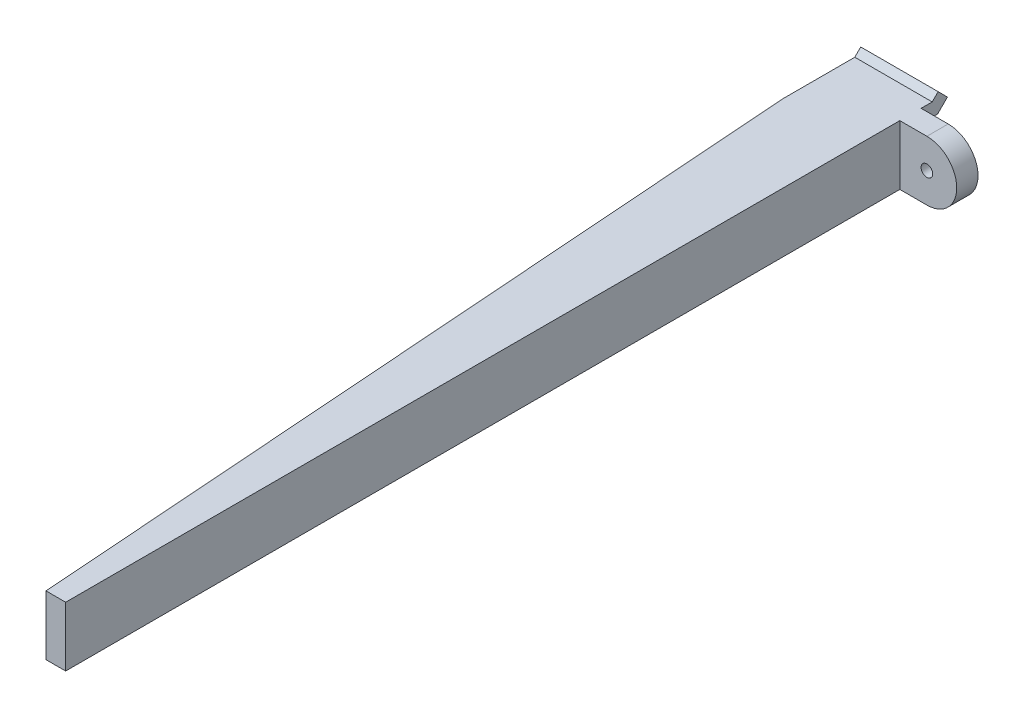
SolidWorks part; units mm, degrees
ref_plane "Front Plane" through (0, 0, 0) normal (0, 0, 1) x (1, 0, 0)
ref_plane "Top Plane" through (0, 0, 0) normal (0, 1, 0) x (1, 0, 0)
ref_plane "Right Plane" through (0, 0, 0) normal (1, 0, 0) x (0, 0, -1)
sketch "Sketch2" plane through (0, 0, 0) normal (0, 0, 1) x (1, 0, 0)
  line L0 (0, 5.9203) -> (0, 8.9503) construction
  line L1 (-5, -5.8182) -> (5, -5.8182)
  line L2 (-5, -5.8182) -> (-5, 8.9503)
  line L3 (-5, 8.9503) -> (5, 8.9503)
  line L4 (5, -5.8182) -> (5, 8.9503)
  line L5 (89.0703, 8.9503) -> (109.0703, 8.9503) construction
  line L7 (33.2703, 5.9203) -> (-18.7297, 5.9203) construction
  line L8 (0, -5.8182) -> (0, -2.7882) construction
  point P0 (0, 0)
  dimension "D1" = 10
extrude "Boss-Extrude1" add sketch "Sketch2" along normal blind 5
sketch "Sketch8" plane through (-5, 0, 0) normal (-1, 0, 0) x (0, 0, 1)
  line L6 (-0.15, 5.7703) -> (0, 5.7703)
  line L7 (0, 8.9503) -> (0, -5.8182) construction
  line L8 (0, 5.7703) -> (0, 4.0703)
  line L9 (0, 4.0703) -> (-0.15, 4.0703)
  line L11 (-0.15, -1.9297) -> (0, -1.9297)
  line L12 (-2.1379, 4.0703) -> (-0.15, 4.0703)
  line L13 (-0.15, 4.0703) -> (-0.15, 5.7703)
  line L14 (-0.15, 5.7703) -> (-1.4337, 5.7703)
  line L15 (-1.4337, 5.7703) -> (-2.2, 6.5366)
  line L16 (-2.2, 6.5366) -> (-3.4021, 5.3345)
  line L17 (-3.4021, 5.3345) -> (-2.1379, 4.0703)
  line L18 (-2.1379, 4.0703) -> (-0.15, 4.0703)
  line L20 (-0.15, 5.7703) -> (-1.4337, 5.7703)
  line L21 (-1.4337, 5.7703) -> (-2.2, 6.5366)
  line L22 (-2.2, 6.5366) -> (-3.4021, 5.3345)
  line L23 (-3.4021, 5.3345) -> (-2.1379, 4.0703)
  line L24 (-2.1379, -1.9297) -> (-0.15, -1.9297)
  line L25 (-0.15, -1.9297) -> (-0.15, -0.2297)
  line L26 (-0.15, -0.2297) -> (-1.4337, -0.2297)
  line L27 (-1.4337, -0.2297) -> (-2.2, 0.5366)
  line L28 (-2.2, 0.5366) -> (-3.4021, -0.6655)
  line L29 (-3.4021, -0.6655) -> (-2.1379, -1.9297)
  line L30 (-2.1379, -1.9297) -> (-0.15, -1.9297)
  line L32 (-0.15, -0.2297) -> (-1.4337, -0.2297)
  line L33 (-1.4337, -0.2297) -> (-2.2, 0.5366)
  line L34 (-2.2, 0.5366) -> (-3.4021, -0.6655)
  line L35 (-3.4021, -0.6655) -> (-2.1379, -1.9297)
  line L37 (-0.15, -0.2297) -> (0, -0.2297)
  line L38 (0, -1.9297) -> (0, -0.2297)
  dimension "D1" = 0.15
  dimension "D2" = 0.15
extrude "Boss-Extrude4" add sketch "Sketch8" against normal up to surface (10 mm away) up to face at (5, 1.566, 2.5)
sketch "Sketch9" plane through (0, 0, 0) normal (0, 0, -1) x (-1, 0, 0)
  line L4 (-5, 8.9503) -> (-5, 5.7703)
  line L5 (-5, 5.7703) -> (5, 5.7703)
  line L6 (5, 5.7703) -> (5, 8.9503)
  line L7 (5, 8.9503) -> (-5, 8.9503)
  line L8 (-5, 8.9503) -> (-5, 5.7703)
  line L10 (5, 5.7703) -> (5, 8.9503)
  line L11 (5, 8.9503) -> (-5, 8.9503)
  line L16 (5, -1.9297) -> (-5, -1.9297)
  line L17 (-5, -1.9297) -> (-5, -5.8182)
  line L18 (-5, -5.8182) -> (5, -5.8182)
  line L19 (5, -5.8182) -> (5, -1.9297)
  line L21 (-5, -1.9297) -> (-5, -5.8182)
  line L22 (-5, -5.8182) -> (5, -5.8182)
  line L23 (5, -5.8182) -> (5, -1.9297)
  line L26 (-5, 5.7703) -> (5, 5.7703)
  line L27 (5, -1.9297) -> (-5, -1.9297)
  dimension "D1" = 0
  dimension "D2" = 0
extrude "Cut-Extrude3" cut sketch "Sketch9" against normal blind 5
sketch "Sketch10" plane through (0, 5.7703, 0) normal (0, 1, 0) x (1, 0, 0)
  line L0 (-5, -5) -> (-5, -10.5)
  line L1 (-5, -10.5) -> (1.3524, -55.7)
  line L2 (1.3524, -55.7) -> (6.3524, -55.7)
  line L3 (-5, -5) -> (5, -5)
  line L4 (-120.9789, 453.7107) -> (412.3545, 453.7107) construction
  line L5 (6.3524, -55.7) -> (6.3524, -49.2)
  line L6 (5, -5) -> (5, -14)
  arc A1 (5, -14) -> (6.3524, -49.2) centre (39.6089, -30.2962) ccw
  dimension "D1" = 172
  dimension "D2" = 45.2
  dimension "D3" = 5
  dimension "D4" = 6.5
  dimension "D5" = 5.5
  dimension "D6" = 9
extrude "Boss-Extrude5" add sketch "Sketch10" against normal up to surface (7.7 mm away) up to face at (0, -1.9297, 1.4311)
ref_plane "Plane1" through (0, 0, 2.75) normal (0, 0, 1) x (1, 0, 0)
sketch "Sketch12" plane through (0, 0, 0) normal (0, 0, 1) x (1, 0, 0)
  line L0 (5, 5.7703) -> (8.5, 5.7703)
  line L1 (8.5, -1.9297) -> (5, -1.9297)
  line L2 (5, -1.9297) -> (5, 5.7703)
  line L3 (1.3524, 5.7703) -> (6.3524, 5.7703) construction
  line L4 (1.3524, -1.9297) -> (6.3524, -1.9297) construction
  line L5 (5, 5.3345) -> (5, 6.5366) construction
  line L6 (6.3524, 5.7703) -> (1.3552, 5.7703) construction
  arc A0 (8.5, 5.7703) -> (8.5, -1.9297) centre (8.5, 1.9203) cw
  circle A1 centre (8.5, 1.9203) radius 0.75
  dimension "D1" = 1.5
  dimension "D2" = 3.5
extrude "Boss-Extrude7" add sketch "Sketch12" along normal up to surface (2.75 mm away) up to plane "Plane1"
fillet "Fillet1" radius 2.5 4 edges at (6.3524, 1.9203, 55.7) (1.3524, 1.9203, 55.7) (6.3524, 1.9203, 49.2) (5, 1.9203, 14)
sketch "Sketch13" plane through (0, 5.7703, 0) normal (0, 1, 0) x (1, 0, 0)
  line L1 (-5, -10.5) -> (12.8873, -10.5)
  line L2 (-5, -10.5) -> (-5, -56.7292)
  line L3 (-5, -56.7292) -> (12.8873, -56.7292)
  line L4 (12.8873, -10.5) -> (12.8873, -56.7292)
extrude "Cut-Extrude4" cut sketch "Sketch13" against normal blind 20
sketch "Sketch15" plane through (0, 0, 10.5) normal (0, 0, 1) x (1, 0, 0)
  line L1 (-5, 5.7703) -> (5, 5.7703)
  line L2 (-5, 5.7703) -> (-5, -1.9297)
  line L3 (-5, -1.9297) -> (5, -1.9297)
  line L4 (5, 5.7703) -> (5, -1.9297)
extrude "Boss-Extrude9" add sketch "Sketch15" along normal blind 100
sketch "Sketch16" plane through (0, 5.7703, 0) normal (0, 1, 0) x (1, 0, 0)
  line L0 (-5, -7.9528) -> (2.4612, -110.5)
  line L1 (-5, -110.5) -> (-5, 1.4337) construction
  line L2 (5, -110.5) -> (-5, -110.5) construction
  line L3 (2.4612, -110.5) -> (-5, -110.5)
  line L4 (-5, -110.5) -> (-5, -7.9528)
extrude "Cut-Extrude5" cut sketch "Sketch16" against normal blind 100
